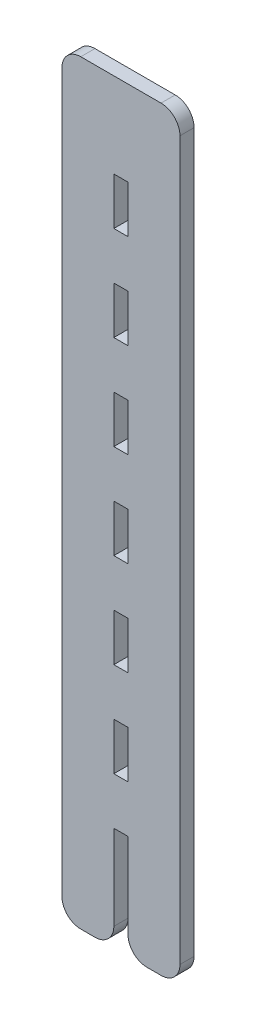
SolidWorks part; units mm, degrees
ref_plane "Plan de face" through (0, 0, 0) normal (0, 0, 1) x (1, 0, 0)
ref_plane "Plan de dessus" through (0, 0, 0) normal (0, 1, 0) x (1, 0, 0)
ref_plane "Plan de droite" through (0, 0, 0) normal (1, 0, 0) x (0, 0, -1)
sketch "Esquisse1" plane through (0, 0, 0) normal (0, 0, 1) x (1, 0, 0)
  line L0 (0, 0) -> (55, 0)
  line L1 (0, 0) -> (125, 0) construction
  line L2 (0, 0) -> (0, 800)
  line L3 (0, 800) -> (125, 800)
  line L4 (125, 0) -> (125, 800)
  line L5 (55, 0) -> (55, 110)
  line L6 (55, 110) -> (70, 110)
  line L7 (70, 110) -> (70, 0)
  line L8 (70, 0) -> (125, 0)
  line L9 (62.5, 460) -> (62.5, 410) construction
  line L10 (55, 160) -> (70, 160)
  line L11 (55, 160) -> (55, 210)
  line L12 (55, 210) -> (70, 210)
  line L13 (70, 160) -> (70, 210)
  line L14 (70, 260) -> (55, 260)
  line L15 (70, 260) -> (70, 310)
  line L16 (70, 310) -> (55, 310)
  line L17 (55, 260) -> (55, 310)
  line L18 (55, 360) -> (70, 360)
  line L19 (55, 360) -> (55, 410)
  line L20 (55, 410) -> (70, 410)
  line L21 (70, 360) -> (70, 410)
  line L22 (70, 460) -> (55, 460)
  line L23 (70, 460) -> (70, 510)
  line L24 (70, 510) -> (55, 510)
  line L25 (55, 460) -> (55, 510)
  line L26 (62.5, 410) -> (62.5, 360) construction
  line L27 (62.5, 360) -> (62.5, 310) construction
  line L28 (62.5, 310) -> (62.5, 260) construction
  line L29 (62.5, 260) -> (62.5, 210) construction
  line L30 (62.5, 210) -> (62.5, 160) construction
  line L31 (62.5, 160) -> (62.5, 110) construction
  line L32 (62.5, 560) -> (62.5, 510) construction
  line L33 (55, 560) -> (70, 560)
  line L34 (55, 560) -> (55, 610)
  line L35 (55, 610) -> (70, 610)
  line L36 (70, 560) -> (70, 610)
  line L37 (55, 660) -> (70, 660)
  line L38 (55, 660) -> (55, 710)
  line L39 (55, 710) -> (70, 710)
  line L40 (70, 660) -> (70, 710)
  line L41 (62.5, 660) -> (62.5, 610) construction
  line L42 (62.5, 610) -> (62.5, 560) construction
  line L43 (62.5, 710) -> (62.5, 660) construction
  line L44 (62.5, 510) -> (62.5, 460) construction
  point P27 (62.5, 800)
  dimension "D1" = 800
  dimension "D2" = 125
  dimension "D3" = 15
  dimension "D4" = 50
  dimension "D5" = 110
extrude "Boss.-Extru.1" add sketch "Esquisse1" along normal blind 15
fillet "Congé1" radius 20 6 edges at (0, 0, 7.5) (125, 0, 7.5) (0, 800, 7.5) (125, 800, 7.5) (70, 0, 7.5) (55, 0, 7.5)
